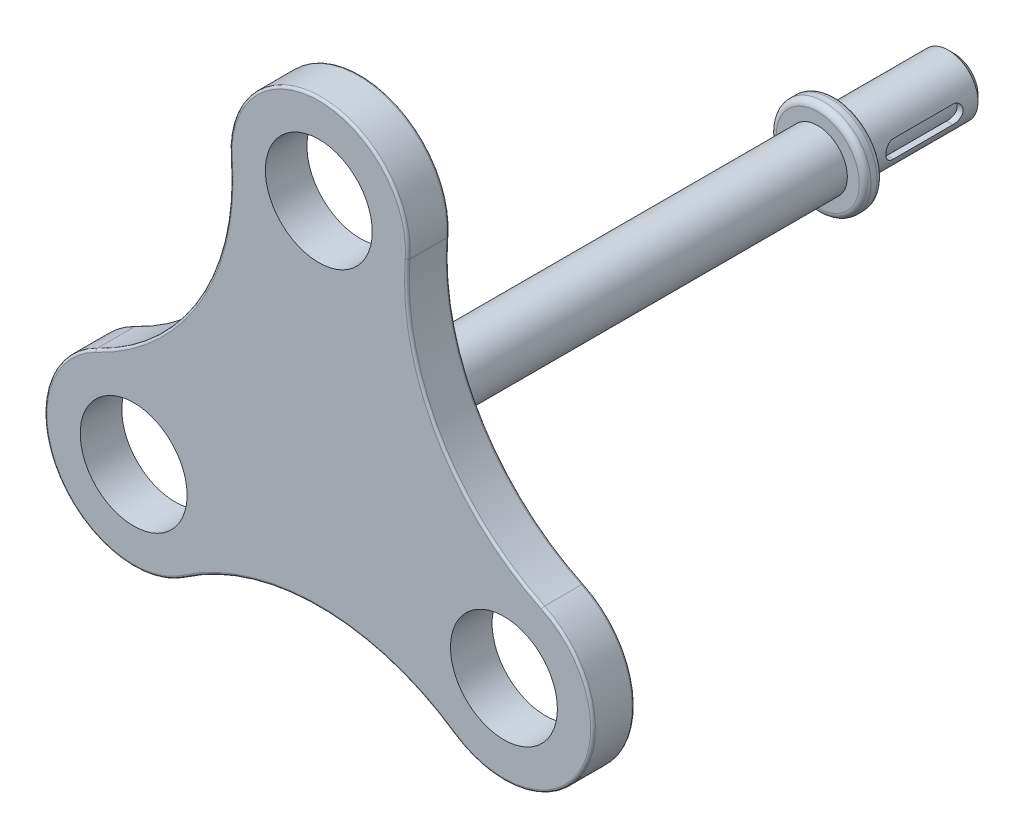
SolidWorks part; units mm, degrees
material "AISI 1020"
ref_plane "Front Plane" through (0, 0, 0) normal (0, 0, 1) x (1, 0, 0)
ref_plane "Top Plane" through (0, 0, 0) normal (0, 1, 0) x (1, 0, 0)
ref_plane "Right Plane" through (0, 0, 0) normal (1, 0, 0) x (0, 0, -1)
sketch "Sketch1" plane through (0, 0, 0) normal (0, 0, 1) x (1, 0, 0)
  circle A0 centre (0, 18) radius 7.5
  circle A1 centre (0, 18) radius 4.5
  circle A2 centre (15.5885, -9) radius 4.5
  circle A3 centre (15.5885, -9) radius 7.5
  circle A4 centre (-15.5885, -9) radius 4.5
  circle A5 centre (-15.5885, -9) radius 7.5
  arc A6 (7.4766, 17.4075) -> (18.8136, -2.2289) centre (27.4141, 15.8275) ccw
  arc A7 (11.3371, -15.1786) -> (-11.3371, -15.1786) centre (0, -31.655) ccw
  arc A8 (-18.8136, -2.2289) -> (-7.4766, 17.4075) centre (-27.4141, 15.8275) ccw
  point P13 (0, 0)
  point P14 (-26.395, -2.2881)
  point P15 (0, 0)
  point P23 (0, 0)
  dimension "D1" = 9
  dimension "D2" = 15
  dimension "D5" = 20
  dimension "D3" = 18
  dimension "D4" = 3
  dimension "D6" = 3
extrude "Boss-Extrude1" add sketch "Sketch1" along normal blind 3.5 contours A0 A1 | A3 A2 | A8 A5 A7 A3 A6 A0 | A5 A4
sketch "Sketch2" plane through (0, 0, 0) normal (0, 0, -1) x (-1, 0, 0)
  circle A0 centre (0, 0) radius 2.5
extrude "Boss-Extrude2" add sketch "Sketch2" along normal blind 50
sketch "Sketch3" plane through (0, 0, -50) normal (0, 0, -1) x (-1, 0, 0)
  circle A0 centre (0, 0) radius 4
extrude "Boss-Extrude3" add sketch "Sketch3" against normal blind 1.5 from offset 10 offset against normal yes
sketch "Sketch5" plane through (0, 0, 0) normal (1, 0, 0) x (0, 0, -1)
  line L0 (42.5, 0) -> (47.5, 0) construction
  line L1 (42.5, 0.75) -> (47.5, 0.75)
  line L2 (42.5, -0.75) -> (47.5, -0.75)
  line L3 (50, -2.5) -> (50, 2.5) construction
  arc A0 (42.5, 0.75) -> (42.5, -0.75) centre (42.5, 0) ccw
  arc A1 (47.5, -0.75) -> (47.5, 0.75) centre (47.5, 0) ccw
  point P2 (45, 0)
  point P8 (0, 0)
  dimension "D1" = 5
  dimension "D2" = 5
  dimension "D3" = 1.5
extrude "Cut-Extrude1" cut sketch "Sketch5" against normal offset from surface (3.146 mm away) 0.5 from offset 5 contours L1 A1 L2 A0
chamfer "Chamfer1" distance 0.5 angle 45 1 edges at (-2.5, 0, -50)
fillet "Fillet1" radius 0.5 2 edges at (-4, 0, -40) (-4, 0, -38.5)
fillet "Fillet2" radius 0.2 12 edges at (-22.0836, -12.75, 0) (-22.0836, -12.75, 3.5) (0, -11.655, 0) (0, -11.655, 3.5) (22.0836, -12.75, 0) (22.0836, -12.75, 3.5) (10.0935, 5.8275, 0) (10.0935, 5.8275, 3.5) (0, 25.5, 0) (0, 25.5, 3.5) (-10.0935, 5.8275, 0) (-10.0935, 5.8275, 3.5)
